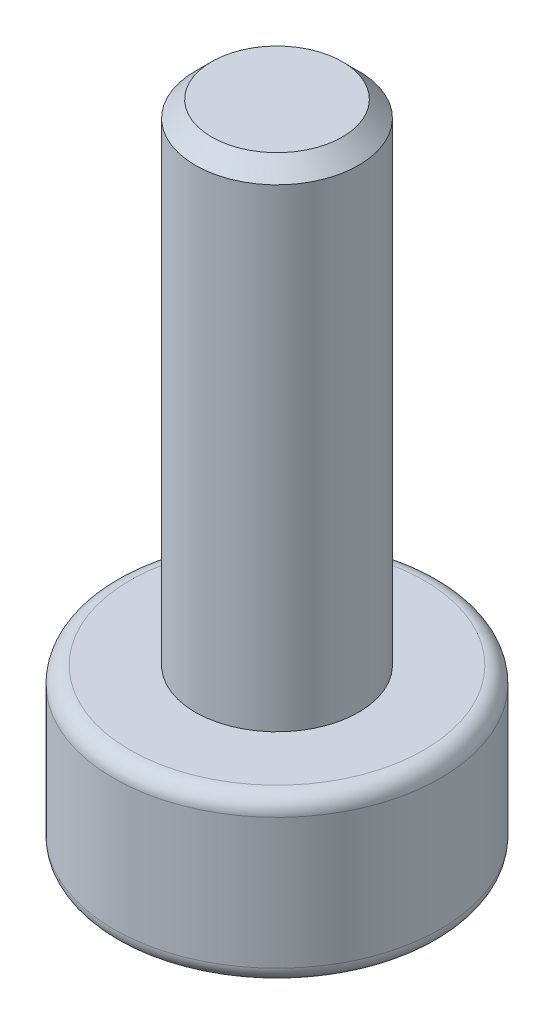
SolidWorks part; units mm, degrees
material "AISI 304"
ref_plane "前视基准面" through (0, 0, 0) normal (0, 0, 1) x (1, 0, 0)
ref_plane "上视基准面" through (0, 0, 0) normal (0, 1, 0) x (1, 0, 0)
ref_plane "右视基准面" through (0, 0, 0) normal (1, 0, 0) x (0, 0, -1)
sketch "草图2" plane through (0, 0, 0) normal (0, 1, 0) x (1, 0, 0)
  circle A0 centre (0, 0) radius 2
  dimension "D1" = 4
extrude "凸台-拉伸1" add sketch "草图2" along normal blind 2
sketch "草图3" plane through (0, 2, 0) normal (0, 1, 0) x (1, 0, 0)
  circle A0 centre (0, 0) radius 1
  dimension "D1" = 2
extrude "凸台-拉伸2" add sketch "草图3" along normal blind 6
fillet "圆角1" radius 0.2 2 edges at (0, 2, 2) (0, 0, 2)
sketch "草图4" plane through (0, 0, 0) normal (0, -1, 0) x (1, 0, 0)
  circle A0 centre (0, 0) radius 0.765
  dimension "D1" = 1.53
extrude "切除-拉伸1" cut sketch "草图4" against normal blind 1.52
chamfer "倒角1" distance 0.1 angle 45 1 edges at (0, 0, -0.765)
chamfer "倒角2" distance 0.2 angle 45 1 edges at (0, 8, 1)
